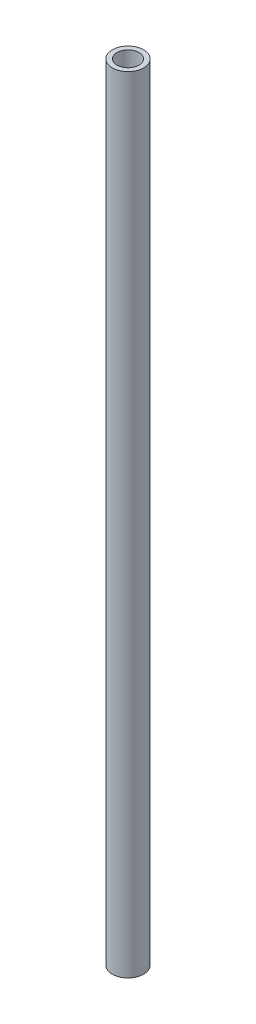
SolidWorks part; units mm, degrees
material "Thornel Mat VMA"
ref_plane "Front Plane" through (0, 0, 0) normal (0, 0, 1) x (1, 0, 0)
ref_plane "Top Plane" through (0, 0, 0) normal (0, 1, 0) x (1, 0, 0)
ref_plane "Right Plane" through (0, 0, 0) normal (1, 0, 0) x (0, 0, -1)
sketch "Sketch1" plane through (0, 0, 0) normal (0, 1, 0) x (1, 0, 0)
  circle A0 centre (0, 0) radius 3.5
  circle A1 centre (0, 0) radius 5
  dimension "D1" = 10
  dimension "D2" = 1.5
extrude "Boss-Extrude1" add sketch "Sketch1" along normal blind 250
